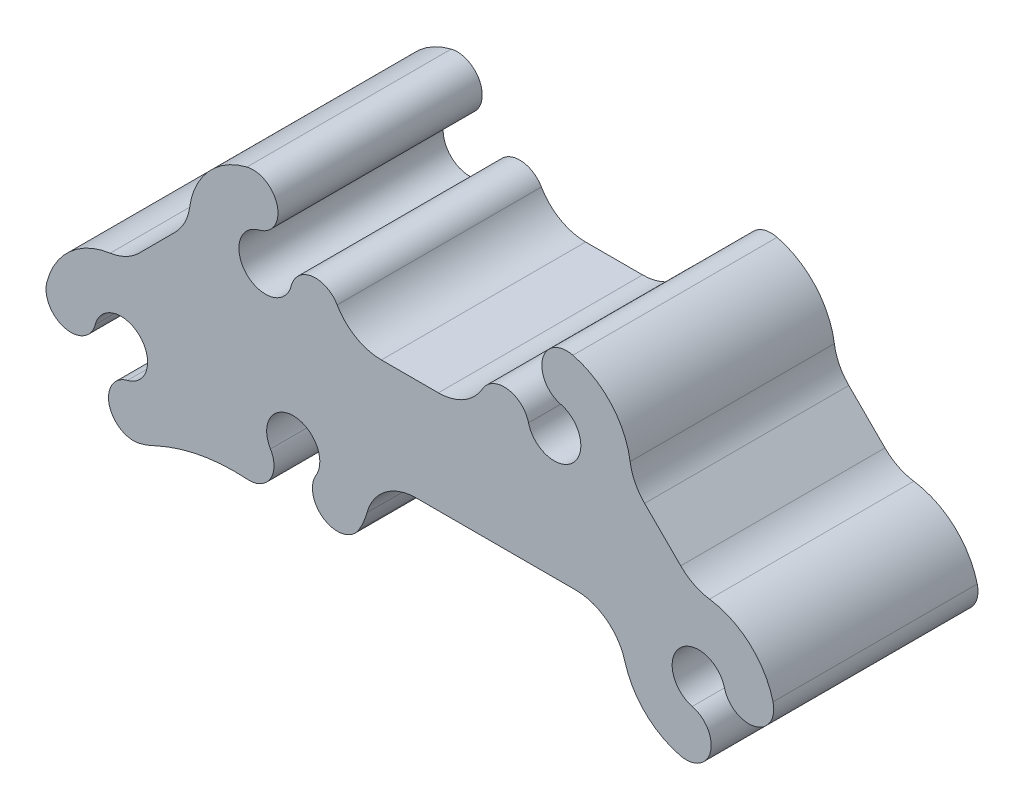
SolidWorks part; units mm, degrees
ref_plane "Front Plane" through (0, 0, 0) normal (0, 0, 1) x (1, 0, 0)
ref_plane "Top Plane" through (0, 0, 0) normal (0, 1, 0) x (1, 0, 0)
ref_plane "Right Plane" through (0, 0, 0) normal (1, 0, 0) x (0, 0, -1)
sketch "Sketch1" plane through (0, 0, 0) normal (0, 0, 1) x (1, 0, 0)
  line L0 (-17.9602, 9.525) -> (17.9605, 9.525) construction
  line L1 (3.5417, 6.35) -> (-3.5417, 6.35)
  line L2 (-29.1844, 7.2799) -> (-33.6682, 2.7898)
  line L3 (0.7827, -6.35) -> (20.6295, -6.35)
  line L4 (0, 6.35) -> (0, -6.3984) construction
  line L5 (-40.3446, 0) -> (40.3446, 0) construction
  line L6 (33.6827, 2.7852) -> (29.1915, 7.268)
  line L7 (-35.9196, -8.4391) -> (-14.5039, -8.4391) construction
  arc A0 (27.3908, 10.8674) -> (29.1915, 7.268) centre (33.6774, 11.7623) ccw
  arc A1 (27.3908, 10.8674) -> (20.2758, 18.7647) centre (17.9605, 9.525) ccw
  arc A2 (20.2758, 18.7647) -> (18.7623, 12.7285) centre (19.5195, 15.7465) ccw
  arc A3 (14.7554, 8.7253) -> (18.7623, 12.7285) centre (17.9589, 9.5258) ccw
  arc A4 (14.7554, 8.7253) -> (9.0417, 9.5262) centre (11.7367, 7.971) ccw
  arc A5 (3.5417, 6.35) -> (9.0417, 9.5262) centre (3.5417, 12.7) ccw
  arc A6 (-9.0417, 9.5262) -> (-3.5417, 6.35) centre (-3.5417, 12.7) ccw
  arc A7 (-9.0417, 9.5262) -> (-14.7555, 8.7248) centre (-11.7367, 7.971) ccw
  arc A8 (-18.8235, 12.7132) -> (-14.7555, 8.7248) centre (-17.9602, 9.525) ccw
  arc A9 (-18.8235, 12.7132) -> (-20.2664, 18.7663) centre (-19.513, 15.7474) ccw
  arc A10 (-20.2664, 18.7663) -> (-27.4001, 10.7932) centre (-17.9602, 9.525) ccw
  arc A11 (-29.1844, 7.2799) -> (-27.4001, 10.7932) centre (-33.6745, 11.7701) ccw
  arc A12 (-37.2647, 0.9904) -> (-33.6682, 2.7898) centre (-38.1615, 7.2768) ccw
  arc A13 (-37.2647, 0.9904) -> (-45.1594, -6.1259) centre (-35.9196, -8.4391) ccw
  arc A14 (-45.1594, -6.1259) -> (-39.1227, -7.6372) centre (-42.1411, -6.8815) ccw
  arc A15 (-35.1195, -11.6427) -> (-39.1227, -7.6372) centre (-35.9196, -8.4391) ccw
  arc A16 (-35.1195, -11.6427) -> (-33.6117, -17.6803) centre (-34.3656, -14.6615) ccw
  arc A17 (-33.6117, -17.6803) -> (-31.6466, -16.9519) centre (-35.9196, -8.4391) ccw
  arc A18 (-20.2199, -14.8407) -> (-31.6466, -16.9519) centre (-21.8246, -38.1341) ccw
  arc A19 (-20.2199, -14.8407) -> (-17.3372, -10.1371) centre (-20.0061, -11.7366) ccw
  arc A20 (-11.7446, -10.2547) -> (-17.3372, -10.1371) centre (-14.5039, -8.4391) ccw
  arc A21 (-11.7446, -10.2547) -> (-6.3396, -13.3359) centre (-9.0086, -11.7366) ccw
  arc A22 (-6.3396, -13.3359) -> (-5.3344, -10.996) centre (-14.5101, -8.4401) ccw
  arc A23 (0.7827, -6.35) -> (-5.3344, -10.996) centre (0.7827, -12.7) ccw
  arc A24 (26.7461, -10.9942) -> (20.6295, -6.35) centre (20.6295, -12.7) ccw
  arc A25 (26.7461, -10.9942) -> (33.6131, -17.6767) centre (35.921, -8.4355) ccw
  arc A26 (33.6131, -17.6767) -> (35.121, -11.6391) centre (34.367, -14.6579) ccw
  arc A27 (39.1246, -7.6354) -> (35.121, -11.6391) centre (35.921, -8.4355) ccw
  arc A28 (39.1246, -7.6354) -> (45.1622, -6.1276) centre (42.1434, -6.8815) ccw
  arc A29 (45.1622, -6.1276) -> (37.2696, 0.9935) centre (35.921, -8.4355) ccw
  arc A30 (33.6827, 2.7852) -> (37.2696, 0.9935) centre (38.1686, 7.2796) ccw
  point P65 (0, 0)
  dimension "D1" = 3.1115
  dimension "D2" = 3.302
  dimension "D6" = 6.35
  dimension "D7" = 3.1115
  dimension "D13" = 6.35
  dimension "D16" = 3.1115
  dimension "D18" = 9.5254
  dimension "D33" = 9.525
  dimension "D36" = 3.1115
  dimension "D37" = 23.3486
  dimension "D42" = 6.35
  dimension "D43" = 6.35
  dimension "D3" = 7.0835
  dimension "D4" = 12.7
  dimension "D5" = 19.8469
  dimension "D8" = 6.35
  dimension "D9" = 8.4355
  dimension "D10" = 35.921
  dimension "D11" = 39.0325
  dimension "D12" = 15.7465
  dimension "D14" = 7.971
  dimension "D15" = 11.7367
  dimension "D17" = 9.5258
  dimension "D19" = 9.525
  dimension "D20" = 11.7701
  dimension "D21" = 33.6745
  dimension "D22" = 15.7474
  dimension "D23" = 2.7898
  dimension "D24" = 7.2799
  dimension "D25" = 20.6295
  dimension "D26" = 6.8815
  dimension "D27" = 42.1434
  dimension "D28" = 34.367
  dimension "D29" = 14.6579
  dimension "D30" = 6.8815
  dimension "D31" = 9.0086
  dimension "D32" = 11.7366
  dimension "D34" = 11.7366
  dimension "D35" = 20.0061
  dimension "D38" = 21.8246
  dimension "D39" = 35.9196
  dimension "D40" = 34.3656
  dimension "D41" = 33.6774
  dimension "D44" = 6.3455
  dimension "D45" = 35.9207
  dimension "D46" = 11.7623
extrude "Boss-Extrude1" add sketch "Sketch1" along normal mid plane 25.4
sketch "Sketch2" plane through (0, 0, 12.7) normal (0, 0, 1) x (1, 0, 0)
  line L0 (-35.9196, -8.4391) -> (-17.9602, 9.525) construction
